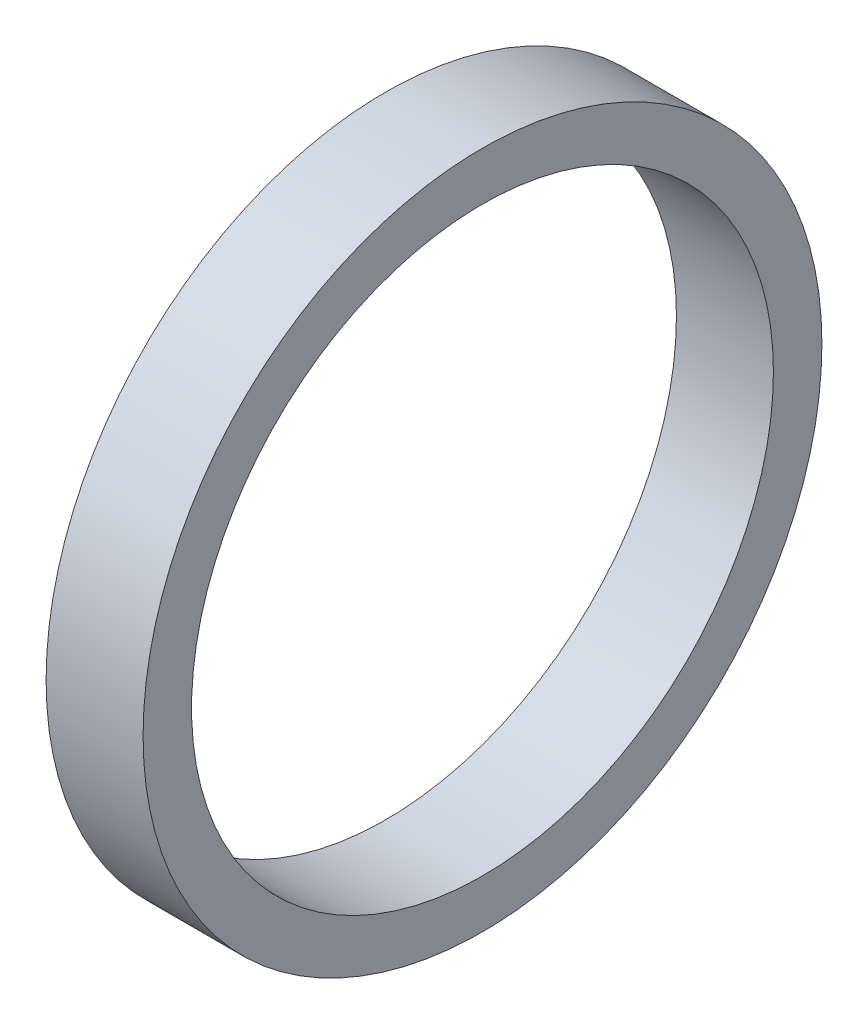
SolidWorks part; units mm, degrees
ref_plane "Front Plane" through (0, 0, 0) normal (0, 0, 1) x (1, 0, 0)
ref_plane "Top Plane" through (0, 0, 0) normal (0, 1, 0) x (1, 0, 0)
ref_plane "Right Plane" through (0, 0, 0) normal (1, 0, 0) x (0, 0, -1)
sketch "Sketch1" plane through (0, 0, 0) normal (1, 0, 0) x (0, 0, -1)
  circle A0 centre (0, 0) radius 6
  circle A1 centre (0, 0) radius 7
  dimension "D1" = 12
  dimension "D2" = 14
extrude "Boss-Extrude1" add sketch "Sketch1" along normal blind 2
